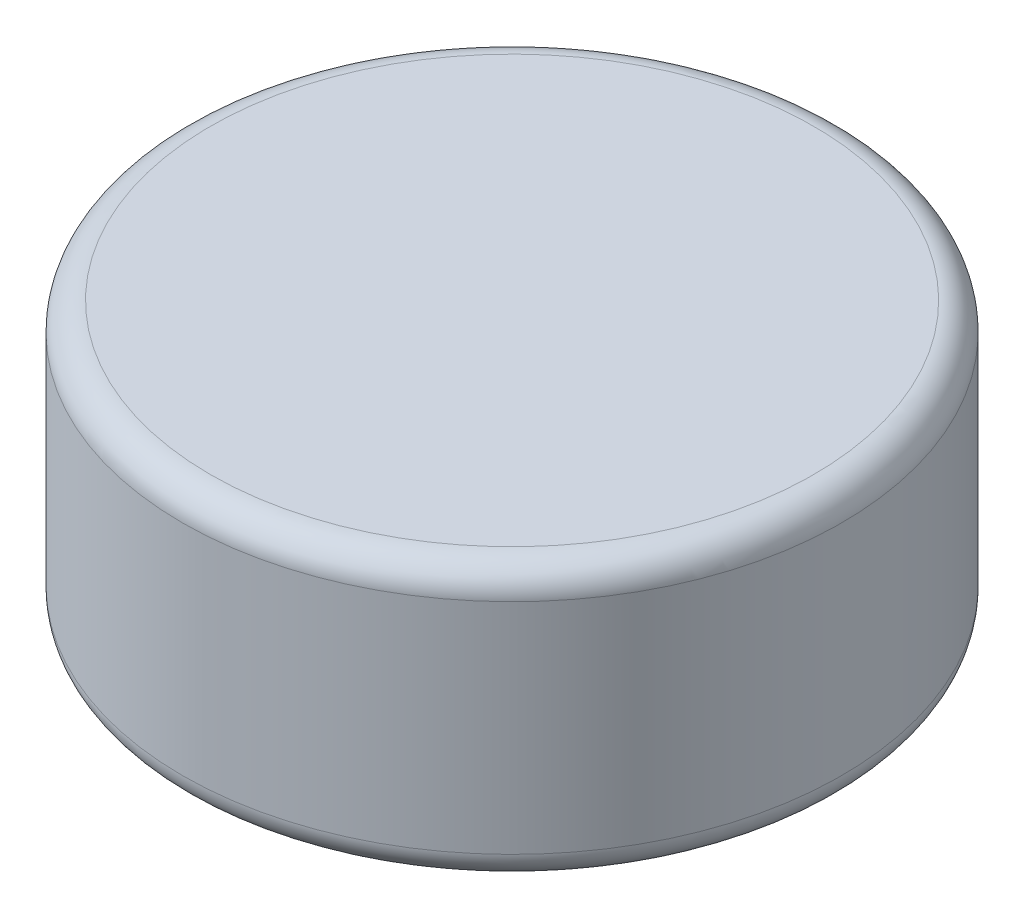
SolidWorks part; units mm, degrees
ref_plane "Front Plane" through (0, 0, 0) normal (0, 0, 1) x (1, 0, 0)
ref_plane "Top Plane" through (0, 0, 0) normal (0, 1, 0) x (1, 0, 0)
ref_plane "Right Plane" through (0, 0, 0) normal (1, 0, 0) x (0, 0, -1)
sketch "Sketch1" plane through (0, 0, 0) normal (0, 1, 0) x (1, 0, 0)
  circle A0 centre (0, 0) radius 3
  dimension "D1" = 6
extrude "Boss-Extrude1" add sketch "Sketch1" along normal blind 2.5
fillet "Fillet1" radius 0.254 2 edges at (0, 0, 3) (0, 2.5, 3)
